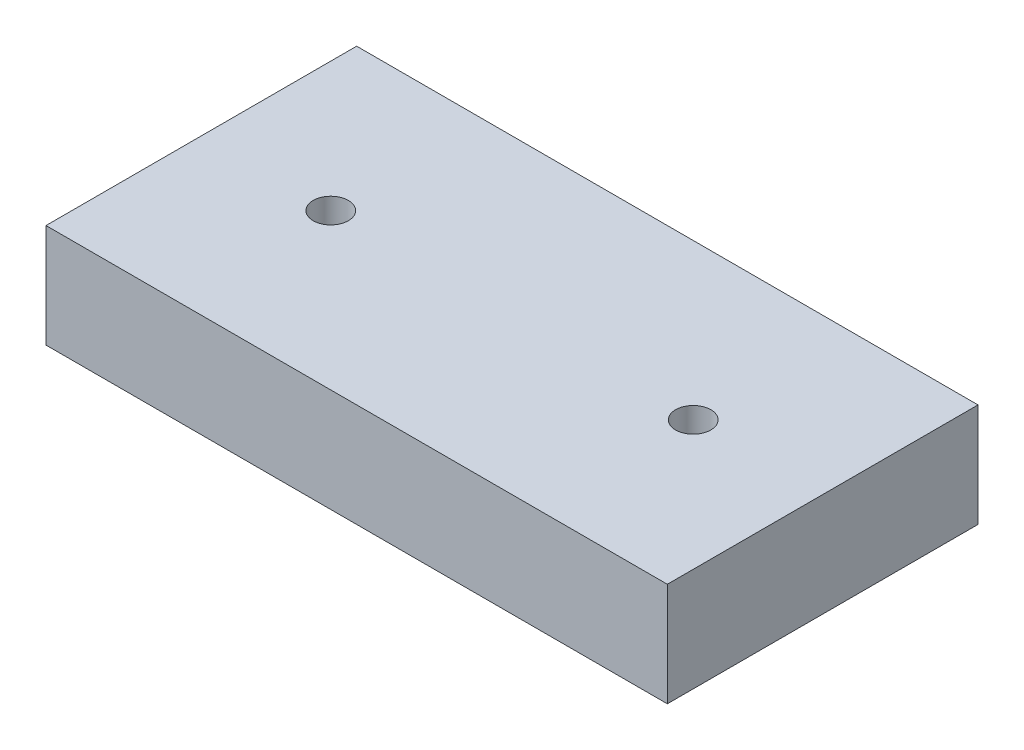
SolidWorks part; units mm, degrees
ref_plane "Front Plane" through (0, 0, 0) normal (0, 0, 1) x (1, 0, 0)
ref_plane "Top Plane" through (0, 0, 0) normal (0, 1, 0) x (1, 0, 0)
ref_plane "Right Plane" through (0, 0, 0) normal (1, 0, 0) x (0, 0, -1)
sketch "Sketch1" plane through (0, 0, 0) normal (0, 1, 0) x (1, 0, 0)
  line L1 (-60, 30) -> (60, 30)
  line L2 (-60, 30) -> (-60, -30)
  line L3 (-60, -30) -> (60, -30)
  line L4 (60, 30) -> (60, -30)
  dimension "D1" = 120
  dimension "D2" = 60
extrude "Boss-Extrude1" add sketch "Sketch1" along normal blind 20 contours L2 L1 L4 L3
sketch "Sketch2" plane through (0, 20, 0) normal (0, 1, 0) x (1, 0, 0)
  line L3 (-35, 0) -> (35, 0) construction
hole_wizard "M8 Tapped Hole2" positions "3DSketch2" profile "Sketch4" tap size "M8" standard "ISO" end condition through all
sketch3d "3DSketch2"
  point P0 (-35, 20, 0)
  point P3 (35, 20, 0)
sketch "Sketch4" plane through (-35, 20, 0) normal (1, 0, 0) x (0, 0, 1)
  line L0 (0, 0) -> (0, 20)
  line L1 (0, 20) -> (3.4, 20)
  line L2 (3.4, 20) -> (3.4, 0)
  line L5 (3.4, 0) -> (0, 0)
  line L11 (0, -6.35) -> (0, 107.95) construction
  dimension "Thru Tap Drill Dia." = 6.8
  dimension "Thru Tap Drill Depth" = 20
cosmetic thread "Hole Thread3" parameters "D2"=8
cosmetic thread "Hole Thread4" parameters "D2"=8
